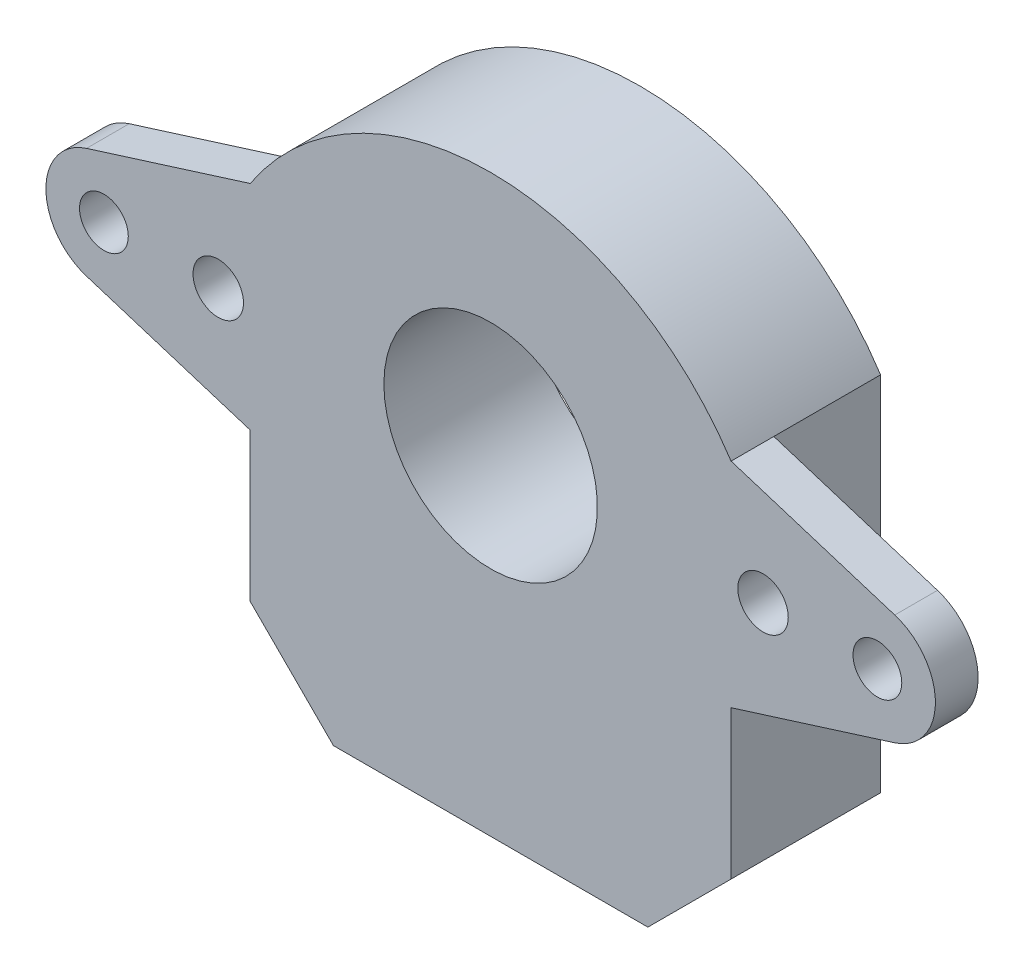
SolidWorks part; units mm, degrees
ref_plane "Front Plane" through (0, 0, 0) normal (0, 0, 1) x (1, 0, 0)
ref_plane "Top Plane" through (0, 0, 0) normal (0, 1, 0) x (1, 0, 0)
ref_plane "Right Plane" through (0, 0, 0) normal (1, 0, 0) x (0, 0, -1)
sketch "Sketch1" plane through (0, 0, 0) normal (0, 0, 1) x (1, 0, 0)
  line L0 (0, -14.1306) -> (0, 20.0694) construction
  line L1 (-9.3503, -14.1306) -> (9.3503, -14.1306)
  line L2 (-14.3, -9.1808) -> (-14.3, 12.346)
  line L4 (14.3, -9.1808) -> (14.3, 12.346)
  line L5 (-12.6013, -10.8795) -> (14.3, 12.346) construction
  line L6 (-14.3, 12.346) -> (12.6013, -10.8795) construction
  line L7 (-14.3, -9.1808) -> (-9.3503, -14.1306)
  line L8 (14.3, -9.1808) -> (9.3503, -14.1306)
  arc A0 (14.3, 12.346) -> (-14.3, 12.346) centre (0, 2.9694) ccw
  point P0 (0, 0)
  point P4 (-16.9046, 11.5424)
  point P7 (0, 1.7812)
  point P15 (0, 0)
  point P16 (0, 2.9694)
  dimension "D1" = 34.2
  dimension "D2" = 28.6
  dimension "D3" = 45
  dimension "D4" = 45
  dimension "D5" = 7
extrude "Boss-Extrude1" add sketch "Sketch1" along normal blind 8.89 contours L2 A0 L4 L8 L1 L7
sketch "Sketch2" plane through (0, 0, 0) normal (0, 0, -1) x (-1, 0, 0)
  line L2 (0, 20.0694) -> (0, -14.1306) construction
  line L3 (9.3503, -14.1306) -> (-9.3503, -14.1306) construction
  line L4 (-14.3, 12.346) -> (14.3, 12.346) construction
  circle A0 centre (0, 5.996) radius 6.35
  arc A1 (14.3, 12.346) -> (-14.3, 12.346) centre (0, 2.9694) ccw construction
  dimension "D1" = 12.7
extrude "Cut-Extrude1" cut sketch "Sketch2" against normal through all
sketch "Sketch3" plane through (0, 0, 8.89) normal (0, 0, 1) x (1, 0, 0)
  line L0 (-24.0342, 2.7047) -> (-14.3, -0.354)
  line L5 (-24.0342, 9.2874) -> (-14.3, 12.346)
  line L6 (-14.3, -9.1808) -> (-14.3, 12.346) construction
  line L8 (0, 12.346) -> (0, -0.354) construction
  line L9 (24.0342, 9.2874) -> (14.3, 12.346)
  line L10 (24.0342, 2.7047) -> (14.3, -0.354)
  line L12 (-14.3, 12.346) -> (14.3, 12.346)
  line L14 (-14.3, -0.354) -> (14.3, -0.354)
  circle A0 centre (0, 5.996) radius 6.35
  circle A8 centre (-16.2, 5.996) radius 1.5
  circle A9 centre (-23, 5.996) radius 1.45
  circle A10 centre (-23, 5.996) radius 3.45
  circle A11 centre (0, 5.996) radius 6.35 construction
  circle A12 centre (23, 5.996) radius 3.45
  circle A13 centre (23, 5.996) radius 1.45
  circle A14 centre (16.2, 5.996) radius 1.5
  dimension "D1" = 2.9
  dimension "D3" = 2
  dimension "D4" = 32.4
  dimension "D5" = 46
  dimension "D2" = 3
extrude "Boss-Extrude2" add sketch "Sketch3" against normal blind 2.54
